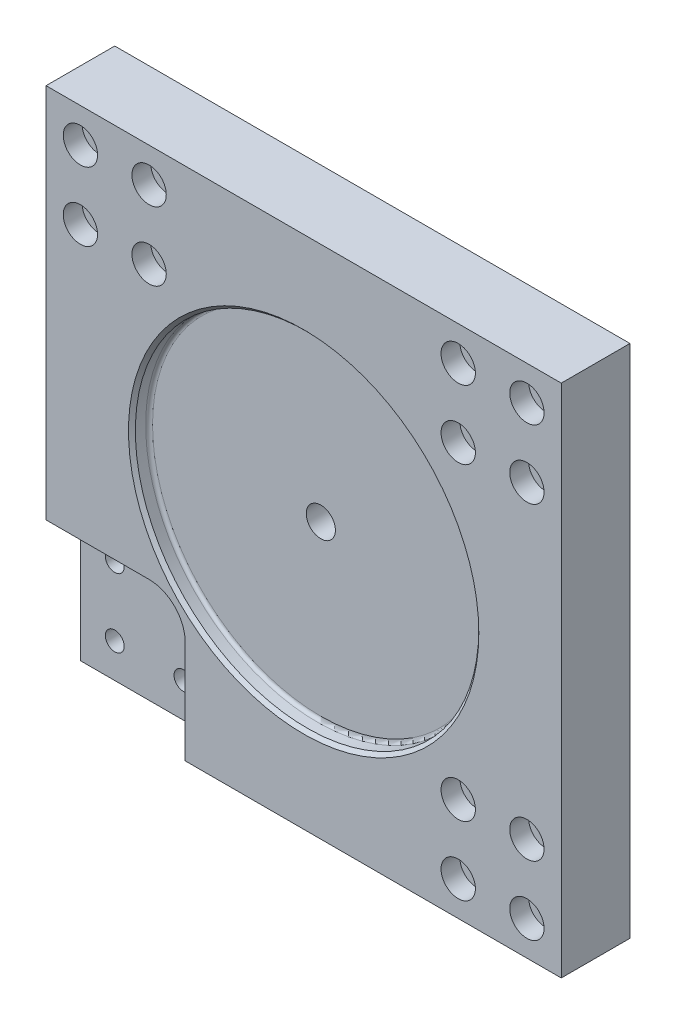
SolidWorks part; units mm, degrees
material "ALUMINIUM,  6082-T6"
ref_plane "Front Plane" through (0, 0, 0) normal (0, 0, 1) x (1, 0, 0)
ref_plane "Top Plane" through (0, 0, 0) normal (0, 1, 0) x (1, 0, 0)
ref_plane "Right Plane" through (0, 0, 0) normal (1, 0, 0) x (0, 0, -1)
sketch "Sketch1" plane through (0, 0, 0) normal (0, 0, 1) x (1, 0, 0)
  line L0 (-75, 75) -> (75, -75) construction
  line L1 (-75, 75) -> (75, 75)
  line L2 (-75, 75) -> (-75, -75)
  line L3 (-75, -75) -> (75, -75)
  line L4 (75, 75) -> (75, -75)
  dimension "D1" = 150
extrude "Boss-Extrude1" add sketch "Sketch1" along normal blind 20
hole_wizard "M10 Tapped Hole1" positions "Sketch2" profile "Sketch3" tap size "M10" standard "ISO" end condition through all
sketch "Sketch2" plane through (0, 0, 20) normal (0, 0, 1) x (1, 0, 0)
  point P0 (0, 0)
sketch "Sketch3" plane through (0, 0, 20) normal (1, 0, 0) x (0, -1, 0)
  line L0 (0, 0) -> (0, 20)
  line L1 (0, 20) -> (4.25, 20)
  line L2 (4.25, 20) -> (4.25, 0)
  line L5 (4.25, 0) -> (0, 0)
  line L11 (0, -6.35) -> (0, 107.95) construction
  dimension "Thru Tap Drill Dia." = 8.5
  dimension "Thru Tap Drill Depth" = 20
cosmetic thread "Hole Thread2" parameters "D2"=10
hole_wizard "CBORE for M5 Hex Socket Head Cap Screw1" positions "Sketch4" profile "Sketch5" counterbore size "M5" standard "ISO" end condition through all
sketch "Sketch4" plane through (0, 0, 20) normal (0, 0, 1) x (1, 0, 0)
  point P0 (-65, 65)
  point P2 (-45, 65)
  point P6 (-65, 45)
  point P24 (65, -45)
  point P25 (65, -65)
  point P26 (45, -65)
  point P28 (45, 65)
  point P29 (65, 65)
  point P30 (65, 45)
  point P43 (45, -45)
  point P47 (-45, 45)
  point P49 (45, 45)
  dimension "D1" = 20
  dimension "D2" = 20
  dimension "D3" = 45
  dimension "D4" = 45
  dimension "D5" = 45
  dimension "D6" = 20
  dimension "D7" = 45
  dimension "D8" = 20
sketch "Sketch5" plane through (-65, 65, 20) normal (1, 0, 0) x (0, -1, 0)
  line L0 (0, 0) -> (0, 20)
  line L1 (0, 20) -> (2.75, 20)
  line L3 (2.75, 20) -> (2.75, 5.5)
  line L4 (2.75, 5.5) -> (5, 5.5)
  line L5 (5, 5.5) -> (5, 0)
  line L7 (5, 0) -> (0, 0)
  line L11 (0, -6.35) -> (0, 107.95) construction
  dimension "Thru Hole Dia." = 5.5
  dimension "Thru Hole Depth" = 20
  dimension "C'Bore Dia." = 10
  dimension "C'Bore Depth" = 5.5
hole_wizard "Ø5.5 (5.5) Diameter Hole1" positions "Sketch8" profile "Sketch9" hole size "Ø5.5" standard "ISO" end condition up to next
sketch "Sketch8" plane through (0, 0, 20) normal (0, 0, 1) x (1, 0, 0)
  line L0 (-65, 45) -> (-65, -45) construction
  line L2 (-45, 45) -> (-45, -45) construction
  line L3 (-45, -45) -> (45, -45) construction
  line L6 (45, -65) -> (-45, -65) construction
  point P0 (-65, -45)
  point P2 (-45, -45)
  point P4 (-45, -65)
  point P6 (-65, -65)
sketch "Sketch9" plane through (-65, -45, 20) normal (1, 0, 0) x (0, -1, 0)
  line L0 (0, 0) -> (0, 20)
  line L1 (0, 20) -> (2.75, 20)
  line L2 (2.75, 20) -> (2.75, 0)
  line L5 (2.75, 0) -> (0, 0)
  line L11 (0, -6.35) -> (0, 107.95) construction
  dimension "Thru Hole Dia." = 5.5
  dimension "Thru Hole Depth" = 20
sketch "Sketch6" plane through (0, 0, 20) normal (0, 0, 1) x (1, 0, 0)
  circle A0 centre (0, 0) radius 50
  dimension "D1" = 100
extrude "Cut-Extrude1" cut sketch "Sketch6" against normal blind 5
fillet "Fillet1" radius 1 1 edges at (50, 0, 15)
chamfer "Chamfer2" distance 1 angle 45 1 edges at (50, 0, 20)
sketch "Sketch7" plane through (0, 0, 20) normal (0, 0, 1) x (1, 0, 0)
  line L5 (-75, -75) -> (-34.5, -75)
  line L6 (-75, -75) -> (-75, -34.5)
  line L7 (-75, -34.5) -> (-45, -34.5)
  line L8 (-34.5, -75) -> (-34.5, -45)
  arc A2 (-45, -34.5) -> (-34.5, -45) centre (-45, -45) cw
  dimension "D2" = 40.5
  dimension "D1" = 10.5
extrude "Cut-Extrude2" cut sketch "Sketch7" against normal blind 10
